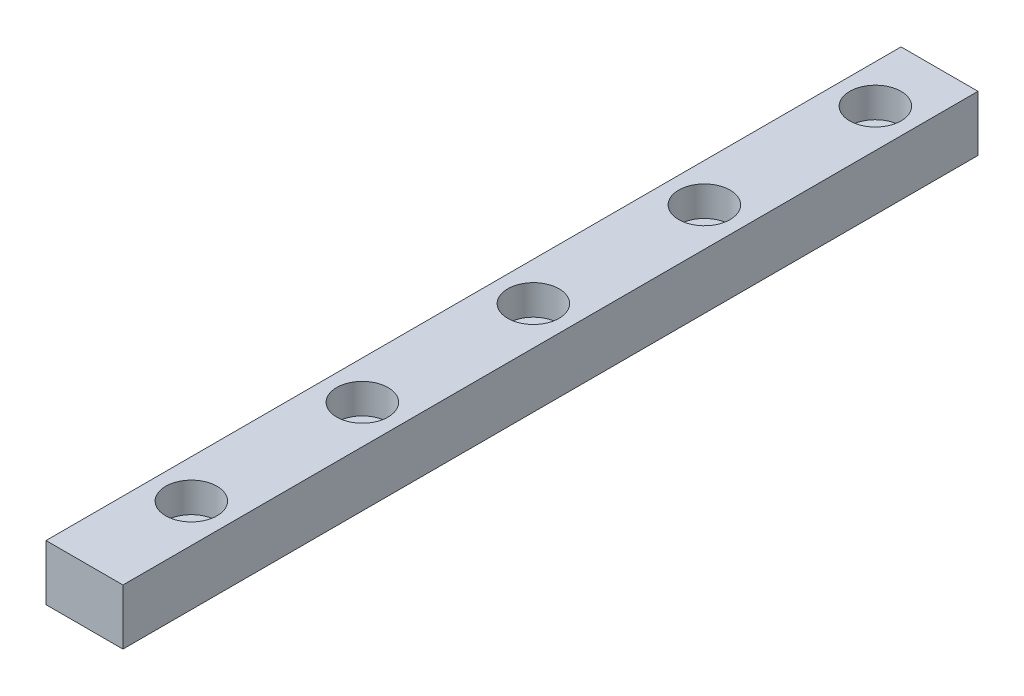
SolidWorks part; units mm, degrees
material "AISI 304"
ref_plane "前视基准面" through (0, 0, 0) normal (0, 0, 1) x (1, 0, 0)
ref_plane "上视基准面" through (0, 0, 0) normal (0, 1, 0) x (1, 0, 0)
ref_plane "右视基准面" through (0, 0, 0) normal (1, 0, 0) x (0, 0, -1)
sketch "草图1" plane through (0, 0, -89.2648) normal (0, 0, 1) x (1, 0, 0)
  line L1 (-4.5, -3.25) -> (4.5, -3.25)
  line L2 (-4.5, -3.25) -> (-4.5, 3.25)
  line L3 (-4.5, 3.25) -> (4.5, 3.25)
  line L4 (4.5, -3.25) -> (4.5, 3.25)
  line L5 (-4.5, -3.25) -> (4.5, 3.25) construction
  line L6 (-4.5, 3.25) -> (4.5, -3.25) construction
  point P0 (0, 0)
  dimension "D1" = 9
  dimension "D2" = 6.5
extrude "凸台-拉伸1" add sketch "草图1" along normal blind 100
sketch "草图2" plane through (0, 3.25, 0) normal (0, 1, 0) x (1, 0, 0)
  line L0 (0, 0) -> (0, -499.5684) construction
  line L1 (4.5, 89.2648) -> (-4.5, 89.2648) construction
  circle A0 centre (0, 81.7648) radius 1.75
  circle A1 centre (0, 61.7648) radius 1.75
  circle A2 centre (0, 41.7648) radius 1.75
  circle A3 centre (0, 21.7648) radius 1.75
  circle A4 centre (0, 1.7648) radius 1.75
  circle A5 centre (0, -18.2352) radius 1.75
  circle A6 centre (0, -38.2352) radius 1.75
  circle A7 centre (0, -58.2352) radius 1.75
  circle A8 centre (0, -78.2352) radius 1.75
  circle A9 centre (0, -98.2352) radius 1.75
  circle A10 centre (0, -118.2352) radius 1.75
  circle A11 centre (0, -138.2352) radius 1.75
  circle A12 centre (0, -158.2352) radius 1.75
  circle A13 centre (0, -178.2352) radius 1.75
  circle A14 centre (0, -198.2352) radius 1.75
  circle A15 centre (0, -218.2352) radius 1.75
  circle A16 centre (0, -238.2352) radius 1.75
  circle A17 centre (0, -258.2352) radius 1.75
  circle A18 centre (0, -278.2352) radius 1.75
  circle A19 centre (0, -298.2352) radius 1.75
  circle A20 centre (0, -318.2352) radius 1.75
  circle A21 centre (0, -338.2352) radius 1.75
  circle A22 centre (0, -358.2352) radius 1.75
  circle A23 centre (0, -378.2352) radius 1.75
  circle A24 centre (0, -398.2352) radius 1.75
  circle A25 centre (0, -418.2352) radius 1.75
  circle A26 centre (0, -438.2352) radius 1.75
  circle A27 centre (0, -458.2352) radius 1.75
  circle A28 centre (0, -478.2352) radius 1.75
  circle A29 centre (0, -498.2352) radius 1.75
  circle A30 centre (0, -518.2352) radius 1.75
  circle A31 centre (0, -538.2352) radius 1.75
  circle A32 centre (0, -558.2352) radius 1.75
  circle A33 centre (0, -578.2352) radius 1.75
  circle A34 centre (0, -598.2352) radius 1.75
  circle A35 centre (0, -618.2352) radius 1.75
  circle A36 centre (0, -638.2352) radius 1.75
  circle A37 centre (0, -658.2352) radius 1.75
  circle A38 centre (0, -678.2352) radius 1.75
  circle A39 centre (0, -698.2352) radius 1.75
  circle A40 centre (0, -718.2352) radius 1.75
  circle A41 centre (0, -738.2352) radius 1.75
  circle A42 centre (0, -758.2352) radius 1.75
  circle A43 centre (0, -778.2352) radius 1.75
  circle A44 centre (0, -798.2352) radius 1.75
  circle A45 centre (0, -818.2352) radius 1.75
  circle A46 centre (0, -838.2352) radius 1.75
  circle A47 centre (0, -858.2352) radius 1.75
  circle A48 centre (0, -878.2352) radius 1.75
  circle A49 centre (0, -898.2352) radius 1.75
  circle A50 centre (0, -918.2352) radius 1.75
  circle A51 centre (0, -938.2352) radius 1.75
  circle A52 centre (0, -958.2352) radius 1.75
  circle A53 centre (0, -978.2352) radius 1.75
  circle A54 centre (0, -998.2352) radius 1.75
  circle A55 centre (0, -1018.2352) radius 1.75
  circle A56 centre (0, -1038.2352) radius 1.75
  circle A57 centre (0, -1058.2352) radius 1.75
  circle A58 centre (0, -1078.2352) radius 1.75
  circle A59 centre (0, -1098.2352) radius 1.75
  dimension "D1" = 3.5
  dimension "D2" = 7.5
  dimension "D4" = 20
  dimension "D3" = 60
extrude "切除-拉伸1" cut sketch "草图2" against normal through all
sketch "草图3" plane through (0, 3.25, 0) normal (0, 1, 0) x (1, 0, 0)
  circle A0 centre (0, 81.7648) radius 3
  circle A1 centre (0, 61.7648) radius 3
  circle A2 centre (0, 41.7648) radius 3
  circle A3 centre (0, 21.7648) radius 3
  circle A4 centre (0, 1.7648) radius 3
  circle A5 centre (0, -18.2352) radius 3
  circle A6 centre (0, -38.2352) radius 3
  circle A7 centre (0, -58.2352) radius 3
  circle A8 centre (0, -78.2352) radius 3
  circle A9 centre (0, -98.2352) radius 3
  circle A10 centre (0, -118.2352) radius 3
  circle A11 centre (0, -138.2352) radius 3
  circle A12 centre (0, -158.2352) radius 3
  circle A13 centre (0, -178.2352) radius 3
  circle A14 centre (0, -198.2352) radius 3
  circle A15 centre (0, -218.2352) radius 3
  circle A16 centre (0, -238.2352) radius 3
  circle A17 centre (0, -258.2352) radius 3
  circle A18 centre (0, -278.2352) radius 3
  circle A19 centre (0, -298.2352) radius 3
  circle A20 centre (0, -318.2352) radius 3
  circle A21 centre (0, -338.2352) radius 3
  circle A22 centre (0, -358.2352) radius 3
  circle A23 centre (0, -378.2352) radius 3
  circle A24 centre (0, -398.2352) radius 3
  circle A25 centre (0, -418.2352) radius 3
  circle A26 centre (0, -438.2352) radius 3
  circle A27 centre (0, -458.2352) radius 3
  circle A28 centre (0, -478.2352) radius 3
  circle A29 centre (0, -498.2352) radius 3
  circle A30 centre (0, -518.2352) radius 3
  circle A31 centre (0, -538.2352) radius 3
  circle A32 centre (0, -558.2352) radius 3
  circle A33 centre (0, -578.2352) radius 3
  circle A34 centre (0, -598.2352) radius 3
  circle A35 centre (0, -618.2352) radius 3
  circle A36 centre (0, -638.2352) radius 3
  circle A37 centre (0, -658.2352) radius 3
  circle A38 centre (0, -678.2352) radius 3
  circle A39 centre (0, -698.2352) radius 3
  circle A40 centre (0, -718.2352) radius 3
  circle A41 centre (0, -738.2352) radius 3
  circle A42 centre (0, -758.2352) radius 3
  circle A43 centre (0, -778.2352) radius 3
  circle A44 centre (0, -798.2352) radius 3
  circle A45 centre (0, -818.2352) radius 3
  circle A46 centre (0, -838.2352) radius 3
  circle A47 centre (0, -858.2352) radius 3
  circle A48 centre (0, -878.2352) radius 3
  circle A49 centre (0, -898.2352) radius 3
  circle A50 centre (0, -918.2352) radius 3
  circle A51 centre (0, -938.2352) radius 3
  circle A52 centre (0, -958.2352) radius 3
  circle A53 centre (0, -978.2352) radius 3
  circle A54 centre (0, -998.2352) radius 3
  circle A55 centre (0, -1018.2352) radius 3
  circle A56 centre (0, -1038.2352) radius 3
  circle A57 centre (0, -1058.2352) radius 3
  circle A58 centre (0, -1078.2352) radius 3
  circle A59 centre (0, -1098.2352) radius 3
  dimension "D1" = 6
  dimension "D3" = 20
  dimension "D2" = 60
extrude "切除-拉伸2" cut sketch "草图3" against normal blind 3.5
